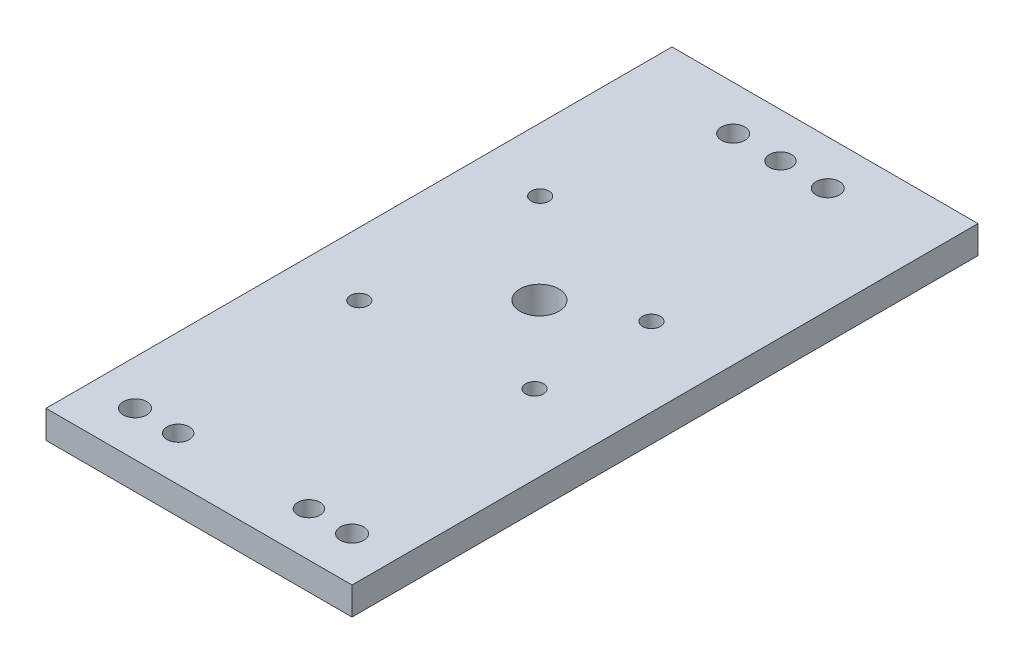
SolidWorks part; units mm, degrees
material "K110"
ref_plane "Front Plane" through (0, 0, 0) normal (0, 0, 1) x (1, 0, 0)
ref_plane "Top Plane" through (0, 0, 0) normal (0, 1, 0) x (1, 0, 0)
ref_plane "Right Plane" through (0, 0, 0) normal (1, 0, 0) x (0, 0, -1)
sketch "Sketch1" plane through (0, 0, 0) normal (0, 1, 0) x (1, 0, 0)
  line L1 (-55, -112.5) -> (55, -112.5)
  line L2 (-55, -112.5) -> (-55, 112.5)
  line L3 (-55, 112.5) -> (55, 112.5)
  line L4 (55, -112.5) -> (55, 112.5)
  line L5 (-55, -112.5) -> (55, 112.5) construction
  line L6 (-55, 112.5) -> (55, -112.5) construction
  point P0 (0, 0)
  dimension "D1" = 225
  dimension "D2" = 110
extrude "Boss-Extrude1" add sketch "Sketch1" against normal blind 10
hole_wizard "M8 Clearance Hole1" positions "Sketch4" profile "Sketch3" hole size "M8" standard "ISO" end condition through all
sketch "Sketch4" plane through (0, 0, 0) normal (0, 1, 0) x (1, 0, 0)
  point P0 (-17, 96.5)
  point P3 (17, 96.5)
  point P6 (-39, -96.5)
  point P9 (39, -96.5)
sketch "Sketch3" plane through (-17, 0, -96.5) normal (1, 0, 0) x (0, 0, 1)
  line L0 (0, 0) -> (0, 10)
  line L1 (0, 10) -> (4.2, 10)
  line L2 (4.2, 10) -> (4.2, 0)
  line L5 (4.2, 0) -> (0, 0)
  line L11 (0, -6.35) -> (0, 107.95) construction
  dimension "Thru Hole Dia." = 8.4
  dimension "Thru Hole Depth" = 10
hole_wizard "Ø8.0mm Dowel Hole1" positions "Sketch7" profile "Sketch6" hole size "Ø8.0" standard "ISO" end condition through all
sketch "Sketch7" plane through (0, 0, 0) normal (0, 1, 0) x (1, 0, 0)
  point P0 (0, 96.5)
  point P3 (-23.5, -96.5)
  point P6 (23.5, -96.5)
sketch "Sketch6" plane through (0, 0, -96.5) normal (1, 0, 0) x (0, 0, 1)
  line L0 (0, 0) -> (0, 10)
  line L1 (0, 10) -> (4, 10)
  line L2 (4, 10) -> (4, 0)
  line L5 (4, 0) -> (0, 0)
  line L11 (0, -6.35) -> (0, 107.95) construction
  dimension "Thru Hole Dia." = 8
  dimension "Thru Hole Depth" = 10
sketch "Sketch8" plane through (0, 0, 0) normal (0, 1, 0) x (1, 0, 0)
  circle A0 centre (0, 9.86) radius 7
  dimension "D1" = 14
extrude "Cut-Extrude1" cut sketch "Sketch8" against normal up to next
hole_wizard "M6 Clearance Hole1" positions "Sketch12" profile "Sketch10" hole size "M6" standard "ISO" end condition through all
sketch "Sketch12" plane through (0, 0, 0) normal (0, 1, 0) x (1, 0, 0)
  point P6 (26.75, 23.36)
  point P9 (26.75, -18.64)
  point P16 (-32.25, 42.36)
  point P19 (-32.25, -22.64)
sketch "Sketch10" plane through (26.75, 0, -23.36) normal (1, 0, 0) x (0, 0, 1)
  line L0 (0, 0) -> (0, 10)
  line L1 (0, 10) -> (3.2, 10)
  line L2 (3.2, 10) -> (3.2, 0)
  line L5 (3.2, 0) -> (0, 0)
  line L11 (0, -6.35) -> (0, 107.95) construction
  dimension "Thru Hole Dia." = 6.4
  dimension "Thru Hole Depth" = 10
